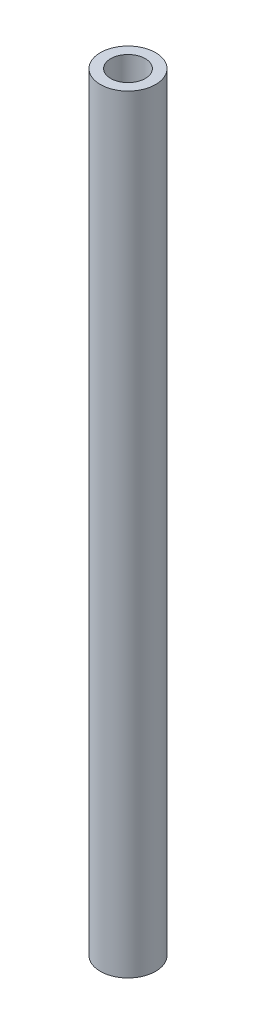
SolidWorks part; units mm, degrees
ref_plane "Front" through (0, 0, 0) normal (0, 0, 1) x (1, 0, 0)
ref_plane "Top" through (0, 0, 0) normal (0, 1, 0) x (1, 0, 0)
ref_plane "Right" through (0, 0, 0) normal (1, 0, 0) x (0, 0, -1)
sketch "Sketch1" plane through (0, 0, 0) normal (0, 1, 0) x (1, 0, 0)
  circle A0 centre (0, 0) radius 1
  dimension "D1" = 2
extrude "Boss-Extrude1" add sketch "Sketch1" along normal blind 27.8
sketch "Sketch2" plane through (0, 27.8, 0) normal (0, 1, 0) x (1, 0, 0)
  line L0 (0, -1) -> (0, 1) construction
  circle A0 centre (0, 0) radius 1 construction
  point P7 (0, 0)
sketch "Sketch3" plane through (0, 0, 0) normal (0, -1, 0) x (1, 0, 0)
  line L0 (0, -1) -> (0, 1) construction
  circle A0 centre (0, 0) radius 1 construction
  point P7 (0, 0)
hole_wizard "M1.6x0.35 Tapped Hole1" positions "3DSketch1" profile "Sketch4" tap size "M1.6x0.35" standard "ANSI Metric"
sketch3d "3DSketch1"
  line L0 (0, 27.8, 0) -> (0, 0, 0) construction
  line L1 (0, 0, -1) -> (0, 0, 1) construction
  point P0 (0, 27.8, 0)
  point P3 (0, 0, 0)
  point P6 (0, 0, 0)
  point P9 (0, 0, 0)
  point P13 (0, 0, 0)
sketch "Sketch4" plane through (0, 27.8, 0) normal (1, 0, 0) x (0, 0, 1)
  line L0 (0, 0) -> (0, 6.3755)
  line L1 (0, 6.3755) -> (0.625, 6)
  line L2 (0.625, 6) -> (0.625, 0)
  line L5 (0.625, 0) -> (0, 0)
  line L10 (0, 6.3755) -> (-0.625, 6) construction
  line L11 (0, -6.35) -> (0, 107.95) construction
  dimension "Tap Drill Dia." = 1.25
  dimension "Tap Drill Depth" = 6
  dimension "Drill Angle" = 118
cosmetic thread "Hole Thread7" parameters "D1"=3.2, "D2"=1.6
cosmetic thread "Hole Thread13" parameters "D1"=3.2, "D2"=1.6
cosmetic thread "Hole Thread14" parameters "D1"=3.2, "D2"=1.6
cosmetic thread "Hole Thread15" parameters "D1"=3.2, "D2"=1.6
cosmetic thread "Hole Thread16" parameters "D1"=3.2, "D2"=1.6
ref_plane "Plane1" through (0, 13.9, 0) normal (0, -1, 0) x (-1, 0, 0)
mirror "Mirror1" about plane through (0, 13.9, 0) normal (0, -1, 0) of "M1.6x0.35 Tapped Hole1"
cosmetic thread "Hole Thread12" parameters "D1"=3.2, "D2"=1.6
